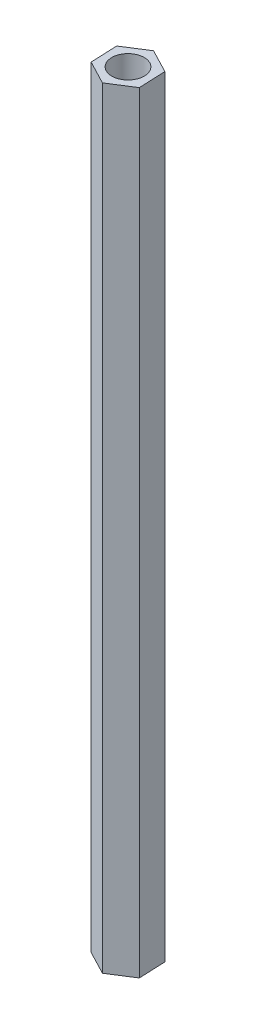
SolidWorks part; units mm, degrees
ref_plane "前视基准面" through (0, 0, 0) normal (0, 0, 1) x (1, 0, 0)
ref_plane "上视基准面" through (0, 0, 0) normal (0, 1, 0) x (1, 0, 0)
ref_plane "右视基准面" through (0, 0, 0) normal (1, 0, 0) x (0, 0, -1)
other "Configuration Table"
sketch "草图1" plane through (0, 0, 0) normal (0, 1, 0) x (1, 0, 0)
  line L1 (3.0707, -1.6034) -> (2.9239, 1.8576)
  line L2 (2.9239, 1.8576) -> (-0.1468, 3.461)
  line L3 (-0.1468, 3.461) -> (-3.0707, 1.6034)
  line L4 (-3.0707, 1.6034) -> (-2.9239, -1.8576)
  line L5 (-2.9239, -1.8576) -> (0.1468, -3.461)
  line L6 (0.1468, -3.461) -> (3.0707, -1.6034)
  circle A0 centre (0, 0) radius 2.1
  circle A1 centre (0, 0) radius 3 construction
extrude "凸台-拉伸1" add sketch "草图1" along normal blind 60
sketch "草图2" plane through (0, 60, 0) normal (0, 1, 0) x (1, 0, 0)
  line L6 (0.1468, -3.461) -> (3.0707, -1.6034)
  line L7 (3.0707, -1.6034) -> (2.9239, 1.8576)
  line L8 (2.9239, 1.8576) -> (-0.1468, 3.461)
  line L9 (-0.1468, 3.461) -> (-3.0707, 1.6034)
  line L10 (-3.0707, 1.6034) -> (-2.9239, -1.8576)
  line L11 (-2.9239, -1.8576) -> (0.1468, -3.461)
  line L12 (0.1468, -3.461) -> (3.0707, -1.6034)
  line L13 (3.0707, -1.6034) -> (2.9239, 1.8576)
  line L14 (2.9239, 1.8576) -> (-0.1468, 3.461)
  line L15 (-0.1468, 3.461) -> (-3.0707, 1.6034)
  line L16 (-3.0707, 1.6034) -> (-2.9239, -1.8576)
  line L17 (-2.9239, -1.8576) -> (0.1468, -3.461)
  line M7 (0.1468, -3.461) -> (3.0707, -1.6034)
  line M8 (3.0707, -1.6034) -> (2.9239, 1.8576)
  line M9 (2.9239, 1.8576) -> (-0.1468, 3.461)
  line M10 (-0.1468, 3.461) -> (-3.0707, 1.6034)
  line M11 (-3.0707, 1.6034) -> (-2.9239, -1.8576)
  line M12 (-2.9239, -1.8576) -> (0.1468, -3.461)
  circle M13 centre (0, 0) radius 2.1
  dimension "D1" = 0
extrude "凸台-拉伸2" add sketch "草图2" along normal blind 40 contours M12 M7 M8 M9 M10 M11 M13
